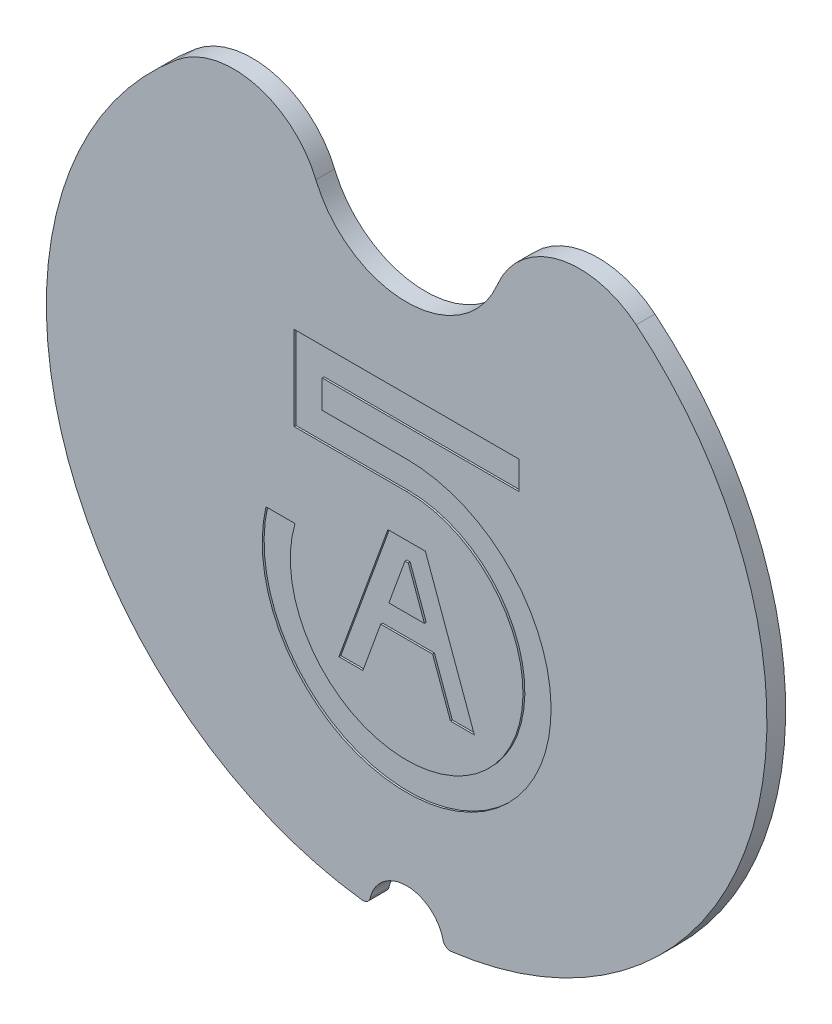
SolidWorks part; units mm, degrees
ref_plane "Alzado" through (0, 0, 0) normal (0, 0, 1) x (1, 0, 0)
ref_plane "Planta" through (0, 0, 0) normal (0, 1, 0) x (1, 0, 0)
ref_plane "Vista lateral" through (0, 0, 0) normal (1, 0, 0) x (0, 0, -1)
sketch "Croquis2" plane through (0, 0, 0) normal (0, 0, 1) x (1, 0, 0)
  line L0 (0, 0) -> (0, 75) construction
  line L1 (-46.1978, 55.875) -> (46.1978, 55.875) construction
  line L2 (0, 0) -> (0, -96.25) construction
  arc A2 (62.128, 75.1422) -> (23.0989, 65.4375) centre (46.1978, 55.875) ccw construction
  arc A3 (-23.0989, 65.4375) -> (-62.128, 75.1422) centre (-46.1978, 55.875) ccw construction
  arc A4 (-23.0989, 65.4375) -> (23.0989, 65.4375) centre (0, 75) ccw construction
  arc A6 (-62.128, 75.1422) -> (62.128, 75.1422) centre (0, 0) ccw construction
  arc A7 (-61.3315, 74.1789) -> (-9.9865, -95.7305) centre (0, 0) ccw
  arc A8 (-24.2538, 64.9594) -> (-61.3315, 74.1789) centre (-46.1978, 55.875) ccw
  arc A9 (-24.2538, 64.9594) -> (24.2538, 64.9594) centre (0, 75) ccw
  arc A10 (61.3315, 74.1789) -> (24.2538, 64.9594) centre (46.1978, 55.875) ccw
  arc A11 (9.9865, -95.7305) -> (-9.9865, -95.7305) centre (0, -96.25) ccw
  arc A12 (9.9865, -95.7305) -> (61.3315, 74.1789) centre (0, 0) ccw
  dimension "D1" = 192.5
  dimension "D2" = 97.5
  dimension "D3" = 25
  dimension "D4" = 25
  dimension "D5" = 25
  dimension "D6" = 47.5
  dimension "D7" = 52.5
  dimension "D8" = 47.5
  dimension "D11" = 10
  dimension "D9" = 75
  dimension "D10" = 19.125
extrude "Saliente-Extruir1" add sketch "Croquis2" along normal blind 5
sketch "Croquis3" plane through (0, 0, 5) normal (0, 0, 1) x (1, 0, 0)
  line L8 (0, -86.25) -> (0, 48.75) construction
  line L12 (30.0606, 27.4545) -> (-30.0606, 27.4545)
  line L13 (-30.0606, 27.4545) -> (-30.0606, 4.9545)
  line L14 (0, 4.9545) -> (-30.0606, 4.9545)
  line L15 (30.0606, 27.4545) -> (30.0606, 19.9545)
  line L16 (30.0606, 19.9545) -> (-22.5606, 19.9545)
  line L17 (-22.5606, 19.9545) -> (-22.5606, 12.4545)
  line L18 (-22.5606, 12.4545) -> (0, 12.4545)
  line L19 (-37.5718, -17.3648) -> (-29.8194, -17.3648)
  line L20 (-5, -6.3553) -> (5, -6.3553)
  line L21 (-5, -6.3553) -> (-18.0838, -42.3027)
  line L22 (-18.0838, -42.3027) -> (-11.6987, -42.3027)
  line L23 (-11.6987, -42.3027) -> (-6.9285, -29.1967)
  line L24 (-6.9285, -29.1967) -> (6.9285, -29.1967)
  line L26 (-4.7447, -23.1967) -> (4.7447, -23.1967)
  line L28 (11.6987, -42.3027) -> (6.9285, -29.1967)
  line L29 (5, -6.3553) -> (18.0838, -42.3027)
  line L30 (18.0838, -42.3027) -> (11.6987, -42.3027)
  line L31 (-4.7447, -23.1967) -> (-0.4348, -11.3553)
  line L32 (-0.4348, -11.3553) -> (0.4348, -11.3553)
  line L33 (4.7447, -23.1967) -> (0.4348, -11.3553)
  arc A1 (9.9865, -95.7305) -> (-9.9865, -95.7305) centre (0, -96.25) ccw construction
  arc A2 (-24.2538, 64.9594) -> (24.2538, 64.9594) centre (0, 75) ccw construction
  circle A3 centre (0, -12.5) radius 50 construction
  arc A4 (0, 12.4545) -> (-37.5718, -17.3648) centre (0, -26.1251) cw
  arc A5 (-29.8194, -17.3648) -> (0, 4.9545) centre (0, -26.1251) ccw
  point P24 (0, -6.3553)
  point P33 (0, -23.1967)
  point P36 (0, -29.1967)
  point P37 (0, -11.3553)
  dimension "D1" = 100
  dimension "D7" = 7.5
  dimension "D2" = 12.5
  dimension "D3" = 7.5
  dimension "D4" = 7.5
  dimension "D5" = 7.5
  dimension "D6" = 7.5
  dimension "D8" = 10
  dimension "D9" = 6
  dimension "D10" = 6
  dimension "D11" = 6
  dimension "D12" = 110
  dimension "D13" = 5
extrude "Cortar-Extruir1" cut sketch "Croquis3" against normal blind 0.5
fillet "Redondeo1" radius 2 1 edges at (-9.9865, -95.7305, 2.5)
fillet "Redondeo2" radius 2 1 edges at (9.9865, -95.7305, 2.5)
